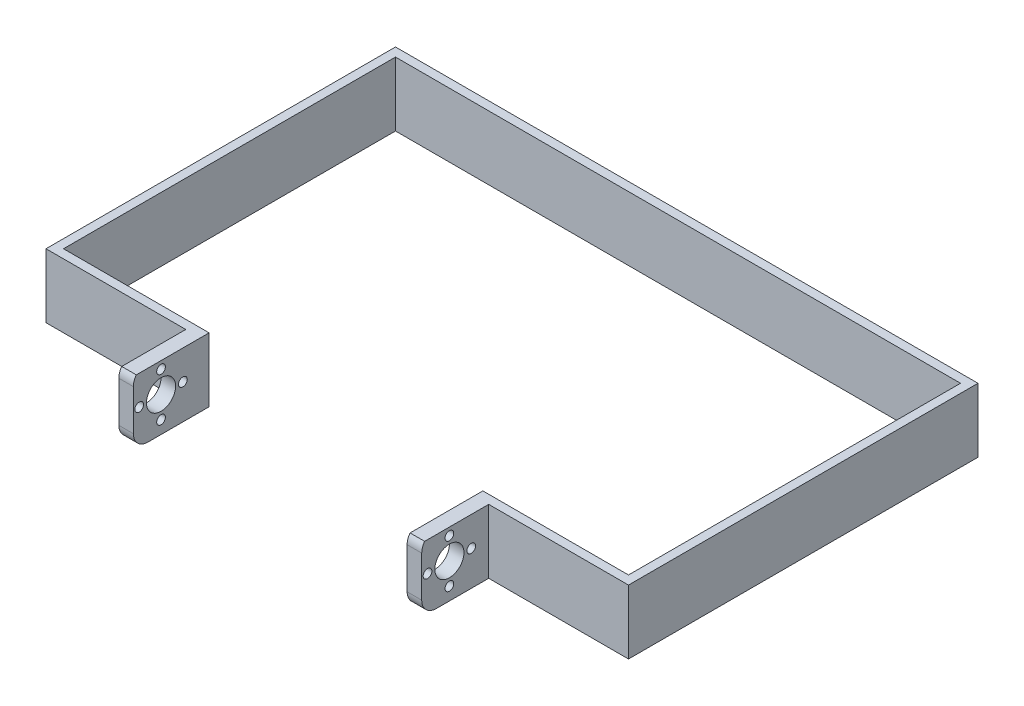
SolidWorks part; units mm, degrees
ref_plane "前视基准面" through (0, 0, 0) normal (0, 0, 1) x (1, 0, 0)
ref_plane "上视基准面" through (0, 0, 0) normal (0, 1, 0) x (1, 0, 0)
ref_plane "右视基准面" through (0, 0, 0) normal (1, 0, 0) x (0, 0, -1)
sketch "草图1" plane through (0, 0, 0) normal (0, 0, 1) x (1, 0, 0)
  line L0 (15, 30) -> (15, 18.3462) construction
  line L3 (-37, 29.1564) -> (67, 29.1564)
  line L5 (-37, 29.1564) -> (-37, -10.8436)
  line L6 (-37, -10.8436) -> (67, -10.8436)
  line L7 (67, -10.8436) -> (67, 29.1564)
  line L8 (-5, 9.1564) -> (-12.7405, 9.1564) construction
  circle A0 centre (15, 9.1564) radius 5
  circle A1 centre (15, 16.6564) radius 1.5
  circle A2 centre (22.5, 9.1564) radius 1.5
  circle A3 centre (15, 1.6564) radius 1.5
  circle A4 centre (7.5, 9.1564) radius 1.5
  point P6 (15, 29.1564)
  point P9 (-37, 9.1564)
  point P23 (15, 9.1564)
  dimension "D3" = 10
  dimension "D4" = 3
  dimension "D1" = 104
  dimension "D2" = 40
  dimension "D5" = 7.5
  dimension "D6" = 4
extrude "凸台-拉伸1" add sketch "草图1" along normal blind 3
sketch "草图2" plane through (0, 0, 3) normal (0, 0, 1) x (1, 0, 0)
  line L4 (15, 29.1564) -> (15, 24.3909) construction
  line L5 (62, 29.1564) -> (62, -10.8436)
  line L6 (-37, 29.1564) -> (-32, 29.1564)
  line L7 (-37, 29.1564) -> (-37, -10.8436)
  line L8 (67, -10.8436) -> (67, 29.1564)
  line L9 (67, 29.1564) -> (-37, 29.1564)
  line L10 (-37, 29.1564) -> (-37, -10.8436)
  line L11 (-37, -10.8436) -> (67, -10.8436)
  line L12 (67, -10.8436) -> (67, 29.1564)
  line L13 (67, 29.1564) -> (-37, 29.1564)
  line L14 (-37, 29.1564) -> (-37, -10.8436)
  line L15 (-37, -10.8436) -> (67, -10.8436)
  line L16 (-37, -10.8436) -> (-32, -10.8436)
  line L17 (-32, 29.1564) -> (-32, -10.8436)
  line M8 (67, -10.8436) -> (67, 29.1564)
  line M9 (67, 29.1564) -> (-37, 29.1564)
  line M10 (-37, 29.1564) -> (-37, -10.8436)
  line M11 (-37, -10.8436) -> (67, -10.8436)
  dimension "D2" = 5
  dimension "D1" = 0
extrude "凸台-拉伸2" add sketch "草图2" along normal blind 20 contours L17 M9 M10 M11 | L5 M9 M11 M8
sketch "草图3" plane through (67, 0, 0) normal (1, 0, 0) x (0, 0, -1)
  line L0 (-35.5831, 9.0691) -> (-32.589, 9.0691) construction
  line L4 (0, -10.8436) -> (0, 29.1564)
  line L5 (0, 29.1564) -> (-23, 29.1564)
  line L6 (-23, 29.1564) -> (-23, -10.8436)
  line L7 (-23, -10.8436) -> (0, -10.8436)
  line L8 (0, -10.8436) -> (0, 29.1564)
  line L9 (0, 29.1564) -> (-23, 29.1564)
  line L10 (-23, 29.1564) -> (-23, -10.8436)
  line L11 (-23, -10.8436) -> (0, -10.8436)
  circle A0 centre (-13.5, 9.0691) radius 5
  circle A5 centre (-13.5, 16.5691) radius 1.5
  circle A9 centre (-6, 9.0691) radius 1.5
  circle A10 centre (-13.5, 1.5691) radius 1.5
  circle A11 centre (-21, 9.0691) radius 1.5
  point P19 (-13.5, 9.0691)
  dimension "D2" = 10
  dimension "D3" = 3
  dimension "D4" = 7.5
  dimension "D6" = 9.5
  dimension "D1" = 0
  dimension "D5" = 4
extrude "切除-拉伸1" cut sketch "草图3" against normal through all both and the other way through all contours A0 L0 | L0 A0 | A11 L0 | L0 A11 | A9 L0 | L0 A9 | A5 | A10
fillet "圆角1" radius 10 4 edges at (64.5, 29.1564, 23) (64.5, -10.8436, 23) (-34.5, 29.1564, 23) (-34.5, -10.8436, 23)
sketch "草图4" plane through (0, 0, 0) normal (0, 0, -1) x (-1, 0, 0)
  line L0 (-15, 29.1564) -> (-15, 9.1564) construction
  line L2 (85, 29.1564) -> (-115, 29.1564)
  line L3 (-67, 29.1564) -> (37, 29.1564) construction
  line L4 (-115, 29.1564) -> (-115, -10.8436)
  line L5 (-115, -10.8436) -> (85, -10.8436)
  line L6 (37, -10.8436) -> (-67, -10.8436) construction
  line L7 (85, 29.1564) -> (85, -10.8436)
  point P12 (-15, -10.8436)
  point P13 (-15, 29.1564)
  dimension "D1" = 100
extrude "凸台-拉伸3" add sketch "草图4" along normal blind 100
sketch "草图5" plane through (0, 29.1564, 0) normal (0, 1, 0) x (1, 0, 0)
  line L2 (-78.1349, 50) -> (-52.0919, 50) construction
  line L3 (15, 100) -> (15, 66.5444) construction
  line L5 (112, 97) -> (-82, 97)
  line L6 (-82, 97) -> (-82, 3)
  line L7 (-85, 100) -> (115, 100) construction
  line L8 (-85, 100) -> (-85, 0) construction
  line L9 (112, 3) -> (62, 3)
  line L10 (112, 97) -> (112, 3)
  line L11 (-32, -3) -> (-32, 3)
  line L12 (-32, -3) -> (62, -3)
  line L13 (62, -3) -> (62, 3)
  line L14 (-32, 3) -> (-82, 3)
  point P12 (-82, 50)
  point P14 (15, 3)
  point P15 (15, 97)
  dimension "D1" = 3
  dimension "D2" = 3
extrude "切除-拉伸2" cut sketch "草图5" against normal blind 100
sketch "草图6" plane through (-37, 0, 0) normal (-1, 0, 0) x (0, 0, 1)
  line L0 (0, 9.1564) -> (6.1346, 9.1564) construction
  line L3 (0, 21.1564) -> (22.798, 21.1564)
  line L4 (0, 29.1564) -> (0, -10.8436) construction
  line L5 (0, -2.8436) -> (22.798, -2.8436)
  line L6 (0, 21.1564) -> (0, 34.7072)
  line L7 (0, 34.7072) -> (26.883, 31.2042)
  line L8 (26.883, 31.2042) -> (22.798, 21.1564)
  line L9 (0, -2.8436) -> (0, -17.3885)
  line L10 (0, -17.3885) -> (28.3202, -11.4604)
  line L11 (28.3202, -11.4604) -> (22.798, -2.8436)
  arc A1 (23, 19.1564) -> (13, 29.1564) centre (13, 19.1564) ccw construction
  dimension "D1" = 12
extrude "切除-拉伸3" cut sketch "草图6" against normal through all both and the other way through all
fillet "圆角2" radius 5 4 edges at (-34.5, -2.8436, 22.798) (-34.5, 21.1564, 22.798) (64.5, -2.8436, 22.798) (64.5, 21.1564, 22.798)
sketch "草图7" plane through (-85, 0, 0) normal (-1, 0, 0) x (0, 0, 1)
  line L0 (0, 21.1564) -> (-100, 21.1564)
  line L1 (-100, -10.8436) -> (-100, 29.1564) construction
  line L3 (-100, -2.8436) -> (0, -2.8436)
  line L5 (0, 21.1564) -> (4.0336, 41.186)
  line L6 (4.0336, 41.186) -> (-112.3553, 36.747)
  line L7 (-112.3553, 36.747) -> (-100, 21.1564)
  line L8 (-100, -2.8436) -> (-111.1643, -19.1196)
  line L9 (-111.1643, -19.1196) -> (4.0336, -17.7122)
  line L10 (4.0336, -17.7122) -> (0, -2.8436)
extrude "切除-拉伸4" cut sketch "草图7" against normal through all both and the other way through all
sketch "草图8" plane through (-85, 0, 0) normal (-1, 0, 0) x (0, 0, 1)
  line L0 (-105.3178, 19.1564) -> (30.018, 19.1564)
  line L1 (30.018, 19.1564) -> (30.018, 27.2766)
  line L2 (30.018, 27.2766) -> (-105.3178, 27.2766)
  line L3 (-105.3178, 27.2766) -> (-105.3178, 19.1564)
  line L4 (18, 21.1564) -> (0, 21.1564) construction
  dimension "D1" = 2
extrude "切除-拉伸5" cut sketch "草图8" against normal through all both and the other way through all
sketch "草图9" plane through (-85, 0, 0) normal (-1, 0, 0) x (0, 0, 1)
  line L0 (0, -2.8436) -> (0, 19.1564) construction
  line L1 (-100, 19.1564) -> (-120, 19.1564)
  line L2 (-100, 19.1564) -> (-100, -2.8436)
  line L3 (-100, -2.8436) -> (-120, -2.8436)
  line L4 (-120, 19.1564) -> (-120, -2.8436)
  dimension "D1" = 22
  dimension "D2" = 120
extrude "凸台-拉伸4" add sketch "草图9" against normal up to surface (200 mm away) up to face at (115, 8.1564, -50)
sketch "草图10" plane through (0, 19.1564, 0) normal (0, 1, 0) x (1, 0, 0)
  line L1 (-82, 97) -> (112, 97)
  line L2 (-82, 97) -> (-82, 117)
  line L3 (-82, 117) -> (112, 117)
  line L4 (112, 97) -> (112, 117)
  line L5 (115, 120) -> (-85, 120) construction
  line L6 (112, 3) -> (112, 97) construction
  point P5 (108.6752, 117)
  dimension "D1" = 3
extrude "切除-拉伸6" cut sketch "草图10" against normal through all both and the other way through all
